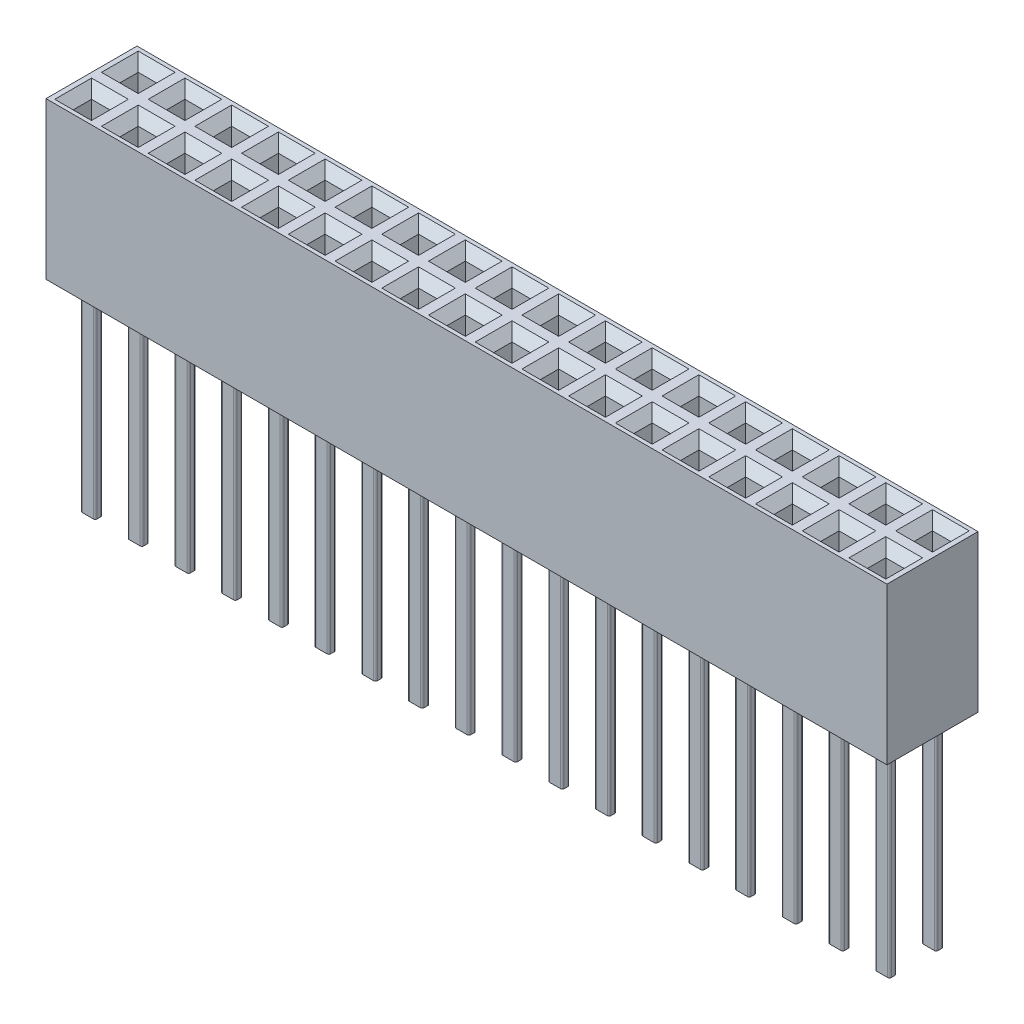
SolidWorks part; units mm, degrees
material "PA Type 6"
ref_plane "Front Plane" through (0, 0, 0) normal (0, 0, 1) x (1, 0, 0)
ref_plane "Top Plane" through (0, 0, 0) normal (0, 1, 0) x (1, 0, 0)
ref_plane "Right Plane" through (0, 0, 0) normal (1, 0, 0) x (0, 0, -1)
ref_plane "Plane1" through (0, -1.65, 0) normal (0, 1, 0) x (1, 0, 0)
sketch "Sketch2" plane through (0, 0, 0) normal (0, 1, 0) x (1, 0, 0)
  line L0 (0, -2.7225) -> (0, 2.7225) construction
  line L1 (-1.27, 2.475) -> (44.45, 2.475)
  line L2 (-1.27, 2.475) -> (-1.27, -2.475)
  line L3 (-1.27, -2.475) -> (44.45, -2.475)
  line L4 (44.45, 2.475) -> (44.45, -2.475)
  line L5 (-5.7805, 0) -> (5.7805, 0) construction
  dimension "D1" = 45.72
  dimension "D2" = 1.27
  dimension "D3" = 4.95
  dimension "D4" = 2.475
extrude "Boss-Extrude1" add sketch "Sketch2" along normal blind 8.51
sketch "Sketch5" plane through (0, 8.51, 0) normal (0, 1, 0) x (1, 0, 0)
  line L1 (0.5, 1.77) -> (-0.5, 1.77)
  line L2 (0.5, 1.77) -> (0.5, 0.77)
  line L3 (0.5, 0.77) -> (-0.5, 0.77)
  line L4 (-0.5, 1.77) -> (-0.5, 0.77)
  line L5 (0, -2.7225) -> (0, 2.7225) construction
  line L7 (-0.5, -0.77) -> (0.5, -0.77)
  line L8 (-0.5, -0.77) -> (-0.5, -1.77)
  line L9 (-0.5, -1.77) -> (0.5, -1.77)
  line L10 (0.5, -0.77) -> (0.5, -1.77)
  dimension "D1" = 1.54
  dimension "D2" = 1
  dimension "D3" = 0.5
  dimension "D4" = 0.77
  dimension "D5" = 2.54
extrude "Cut-Extrude1" cut sketch "Sketch5" against normal blind 5
chamfer "Chamfer1" distance 0.5 angle 45 8 edges at (-0.5, 8.51, -1.27) (0, 8.51, -0.77) (0.5, 8.51, -1.27) (0, 8.51, -1.77) (-0.5, 8.51, 1.27) (0, 8.51, 0.77) (0.5, 8.51, 1.27) (0, 8.51, 1.77)
pattern_linear "LPattern3" count 18 spacing 2.54 along (1, 0, 0) of "Chamfer1", "Cut-Extrude1"
sketch "Sketch8" plane through (0, 0, 0) normal (0, 1, 0) x (1, 0, 0)
  line L0 (0, -2.7225) -> (0, 2.7225) construction
  line L1 (-0.3, -1.47) -> (0.3, -1.47)
  line L2 (-0.4, -1.37) -> (-0.4, -1.17)
  line L3 (-0.3, -1.07) -> (0.3, -1.07)
  line L4 (0.4, -1.37) -> (0.4, -1.17)
  line L6 (-0.4, -1.27) -> (0.4, -1.27) construction
  arc A0 (-0.3, -1.47) -> (-0.4, -1.37) centre (-0.3, -1.37) cw
  arc A1 (0.3, -1.47) -> (0.4, -1.37) centre (0.3, -1.37) ccw
  arc A2 (0.3, -1.07) -> (0.4, -1.17) centre (0.3, -1.17) cw
  arc A3 (-0.4, -1.17) -> (-0.3, -1.07) centre (-0.3, -1.17) cw
  point P10 (-0.4, -1.47)
  point P13 (0.4, -1.47)
  point P16 (0.4, -1.07)
  dimension "D5" = 0.1
  dimension "D1" = 0.4
  dimension "D2" = 0.8
  dimension "D3" = 0.4
  dimension "D4" = 1.27
extrude "Boss-Extrude2" add sketch "Sketch8" against normal blind 11
sketch "Sketch10" plane through (0, -1.65, 0) normal (0, 1, 0) x (1, 0, 0)
  circle A0 centre (0, -1.27) radius 0.75
  dimension "D1" = 1.5
  dimension "D2" = 1.27
extrude "Boss-Extrude3" [suppressed] add sketch "Sketch10" along normal blind 0.1
fillet "Fillet2" [suppressed] radius 0.4
pattern_linear "LPattern1" count 18 spacing 2.54 along (1, 0, 0) count 2 spacing 2.54 along (0, 0, -1) of "Boss-Extrude2", "Fillet2", "Boss-Extrude3"
equation "\"D1@Sketch2\"=2.54 * 18"
equation "\"D4@Sketch2\"=\"D3@Sketch2\"/2"
